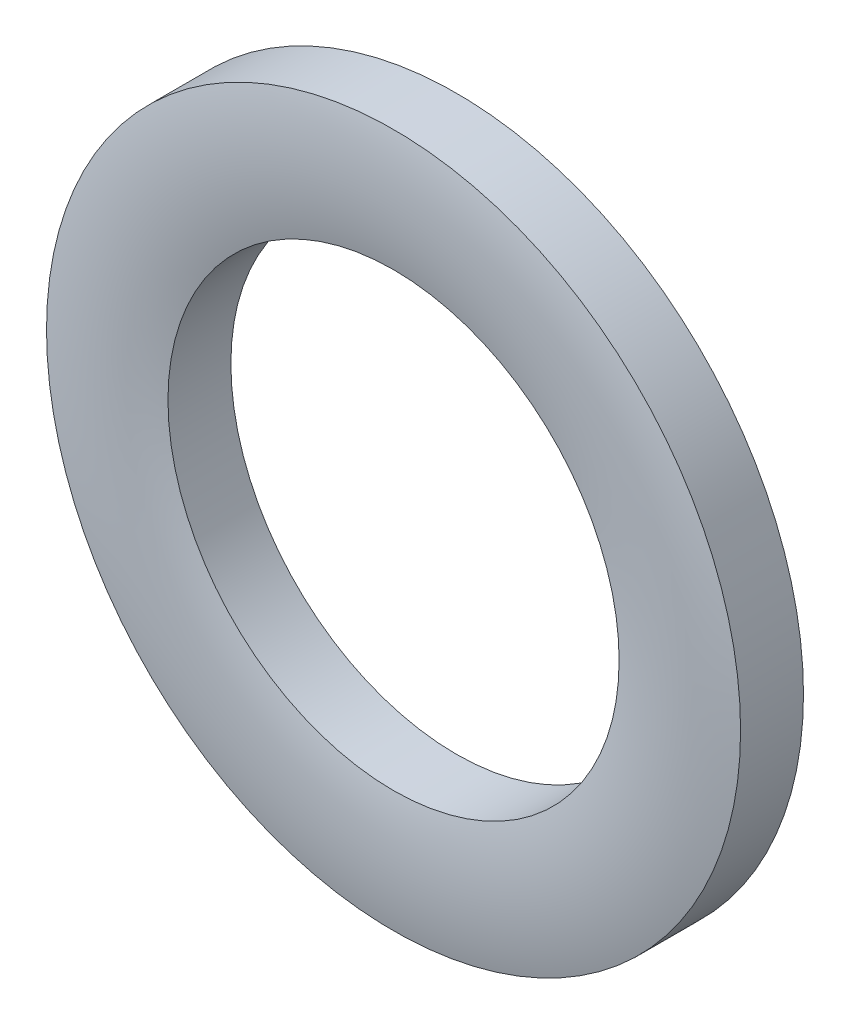
SolidWorks part; units mm, degrees
ref_plane "Front Plane" through (0, 0, 0) normal (0, 0, 1) x (1, 0, 0)
ref_plane "Top Plane" through (0, 0, 0) normal (0, 1, 0) x (1, 0, 0)
ref_plane "Right Plane" through (0, 0, 0) normal (1, 0, 0) x (0, 0, -1)
sketch "Sketch1" plane through (0, 0, 0) normal (0, 0, 1) x (1, 0, 0)
  circle A0 centre (0, 0) radius 6.5
  circle A1 centre (0, 0) radius 10
  dimension "ID" = 13
  dimension "OD" = 20
sketch "Sketch2" plane through (0, 0, 0) normal (1, 0, 0) x (0, 0, -1)
  line L0 (-1, 10) -> (1, 10) construction
  line L1 (-1, 0) -> (1, 0) construction
  point P2 (0, 10)
  dimension "Thickness Range" = 2
sketch "Sketch3" plane through (0, 0, 0) normal (1, 0, 0) x (0, 0, -1)
  line L0 (1, 10) -> (-0.8126, 10)
  line L1 (1, 6.5) -> (-0.8126, 6.5)
  line L2 (1, 6.5) -> (1, 10)
  line L3 (-1, 10) -> (-1, 6.5) construction
  arc A0 (-0.8126, 6.5) -> (-0.8126, 10) centre (7.2647, 8.25) cw
  point P9 (0, 6.5)
  dimension "D1" = 0.1874
revolve "Revolve1" add sketch "Sketch3" angle 360 about L1
equation "\"D1@Sketch3\"=\"Thickness Range@Sketch2\"*.0937"
